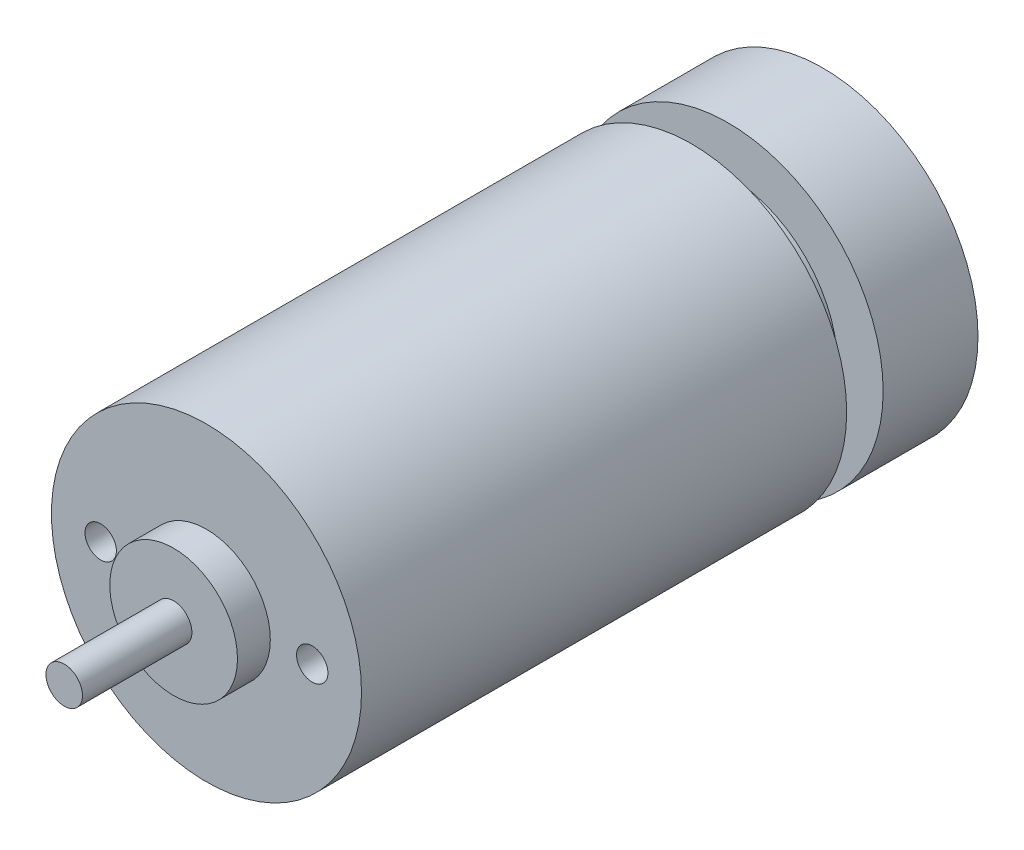
SolidWorks part; units mm, degrees
ref_plane "Ebene vorne" through (0, 0, 0) normal (0, 0, 1) x (1, 0, 0)
ref_plane "Ebene oben" through (0, 0, 0) normal (0, 1, 0) x (1, 0, 0)
ref_plane "Ebene rechts" through (0, 0, 0) normal (1, 0, 0) x (0, 0, -1)
sketch "Skizze1" plane through (0, 0, 0) normal (0, 0, 1) x (1, 0, 0)
  circle A0 centre (0, 0) radius 21.25
  dimension "D1" = 42.5
extrude "Aufsatz-Linear austragen1" add sketch "Skizze1" along normal blind 66.5
sketch "Skizze2" plane through (0, 0, 66.5) normal (0, 0, 1) x (1, 0, 0)
  circle A0 centre (0, 0) radius 8.75
  dimension "D1" = 17.5
extrude "Aufsatz-Linear austragen2" add sketch "Skizze2" along normal blind 4.5
sketch "Skizze3" plane through (0, 0, 71) normal (0, 0, 1) x (1, 0, 0)
  circle A0 centre (0, 0) radius 2.5
  dimension "D1" = 5
extrude "Aufsatz-Linear austragen3" add sketch "Skizze3" along normal blind 15
sketch "Skizze4" plane through (0, 0, 66.5) normal (0, 0, 1) x (1, 0, 0)
  line L0 (-14.5, 0) -> (14.5, 0)
  circle A0 centre (-14.5, 0) radius 2.15
  circle A1 centre (14.5, 0) radius 2.15
  point P4 (0, 0)
  dimension "D2" = 4.3
  dimension "D1" = 29
extrude "Schnitt-Linear austragen1" cut sketch "Skizze4" against normal blind 10
sketch "Skizze5" plane through (0, 0, 0) normal (0, 0, -1) x (-1, 0, 0)
  circle A0 centre (0, 0) radius 15
  dimension "D1" = 30
extrude "Aufsatz-Linear austragen4" add sketch "Skizze5" along normal blind 5 contours A0
sketch "Skizze6" plane through (0, 0, -5) normal (0, 0, -1) x (-1, 0, 0)
  circle A0 centre (0, 0) radius 21.25
  dimension "D1" = 42.5
extrude "Aufsatz-Linear austragen5" add sketch "Skizze6" along normal blind 13
